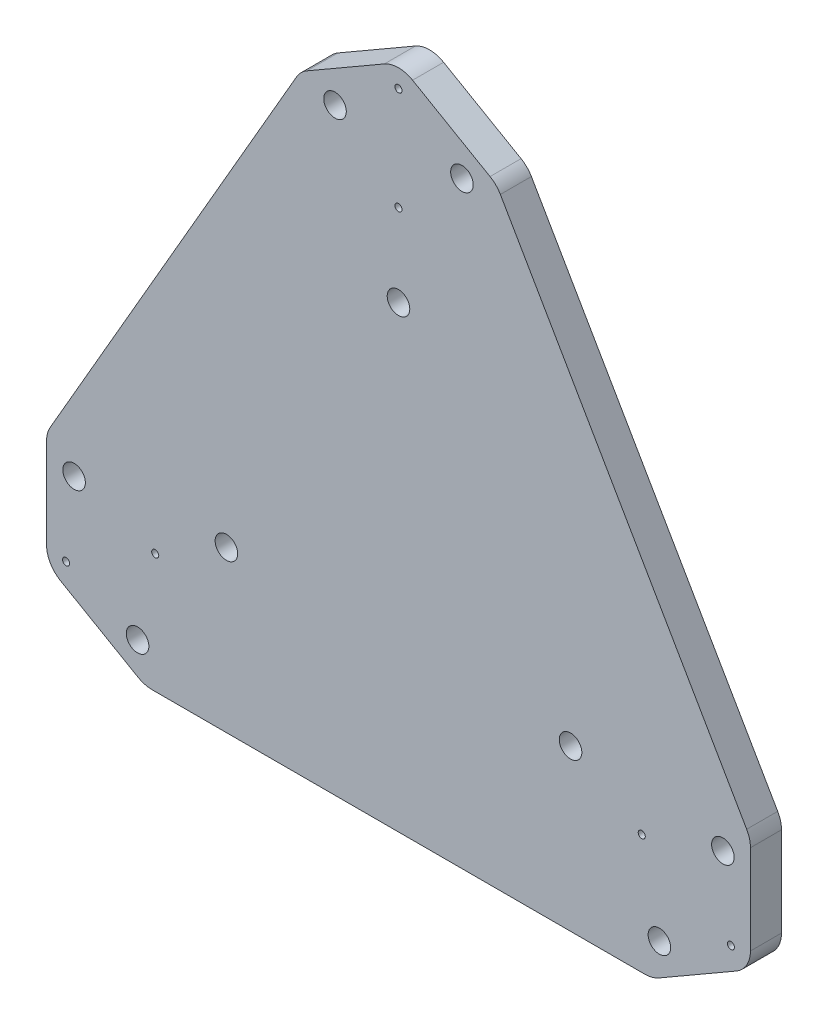
SolidWorks part; units mm, degrees
ref_plane "Plan de face" through (0, 0, 0) normal (0, 0, 1) x (1, 0, 0)
ref_plane "Plan de dessus" through (0, 0, 0) normal (0, 1, 0) x (1, 0, 0)
ref_plane "Plan de droite" through (0, 0, 0) normal (1, 0, 0) x (0, 0, -1)
sketch "Esquisse1" plane through (0, 0, 0) normal (0, 0, 1) x (1, 0, 0)
  line L0 (0, 136.0815) -> (0, 0) construction
  line L1 (0, 0) -> (117.85, -68.0407) construction
  line L2 (0, 0) -> (-117.85, -68.0407) construction
  line L3 (-115, -40.4145) -> (-92.5, -79.3857) construction
  line L4 (-22.5, 119.8002) -> (22.5, 119.8002) construction
  line L5 (92.5, -79.3857) -> (115, -40.4145) construction
  line L6 (34.7782, 124.0023) -> (124.7782, -31.8823)
  line L7 (124.7782, -31.8823) -> (124.7782, -72.0407)
  line L8 (34.7782, 124.0023) -> (0, 144.0815)
  line L9 (0, 136.0815) -> (0, 159.5946) construction
  line L10 (61, -35.2184) -> (132.0567, -76.243) construction
  line L11 (90, -92.1199) -> (-90, -92.1199)
  line L12 (-90, -92.1199) -> (-124.7782, -72.0407)
  line L13 (90, -92.1199) -> (124.7782, -72.0407)
  line L14 (-124.7782, -31.8823) -> (-34.7782, 124.0023)
  line L15 (-34.7782, 124.0023) -> (0, 144.0815)
  line L16 (-124.7782, -31.8823) -> (-124.7782, -72.0407)
  circle A0 centre (-117.85, -68.0407) radius 1.25
  circle A1 centre (117.85, -68.0407) radius 1.25
  circle A2 centre (0, 136.0815) radius 1.25
  circle A3 centre (0, 0) radius 136.0815 construction
  circle A4 centre (-86.2401, -49.7907) radius 1.25
  circle A5 centre (0, 0) radius 99.5815 construction
  circle A6 centre (0, 99.5815) radius 1.25
  circle A7 centre (86.2401, -49.7907) radius 1.25
  circle A8 centre (-61, -35.2184) radius 4
  circle A9 centre (0, 70.4367) radius 4
  circle A10 centre (61, -35.2184) radius 4
  circle A11 centre (0, 0) radius 70.4367 construction
  circle A12 centre (22.5, 119.8002) radius 4
  circle A13 centre (-22.5, 119.8002) radius 4
  circle A14 centre (-115, -40.4145) radius 4
  circle A15 centre (-92.5, -79.3857) radius 4
  circle A16 centre (92.5, -79.3857) radius 4
  circle A17 centre (115, -40.4145) radius 4
  point P51 (0, 0)
  dimension "D1" = 2.5
  dimension "D2" = 2.5
  dimension "D3" = 2.5
  dimension "D6" = 235.7
  dimension "D7" = 2.5
  dimension "D8" = 36.5
  dimension "D9" = 2.5
  dimension "D10" = 2.5
  dimension "D11" = 8
  dimension "D12" = 8
  dimension "D13" = 8
  dimension "D14" = 122
  dimension "D15" = 122
  dimension "D16" = 122
  dimension "D26" = 8
  dimension "D27" = 8
  dimension "D28" = 8
  dimension "D29" = 8
  dimension "D30" = 8
  dimension "D31" = 8
  dimension "D4" = 120
  dimension "D5" = 120
  dimension "D17" = 45
  dimension "D18" = 22.5
  dimension "D19" = 45
  dimension "D20" = 22.5
  dimension "D21" = 45
  dimension "D22" = 22.5
  dimension "D23" = 185
  dimension "D24" = 185
  dimension "D25" = 185
  dimension "D32" = 180
  dimension "D33" = 90
  dimension "D34" = 8
  dimension "D35" = 8
  dimension "D36" = 3
extrude "Boss.-Extru.1" add sketch "Esquisse1" along normal blind 11
fillet "Congé1" radius 10 9 edges at (90, -92.1199, 5.5) (124.7782, -31.8823, 5.5) (34.7782, 124.0023, 5.5) (-34.7782, 124.0023, 5.5) (-124.7782, -31.8823, 5.5) (-124.7782, -72.0407, 5.5) (124.7782, -72.0407, 5.5) (0, 144.0815, 5.5) (-90, -92.1199, 5.5)
